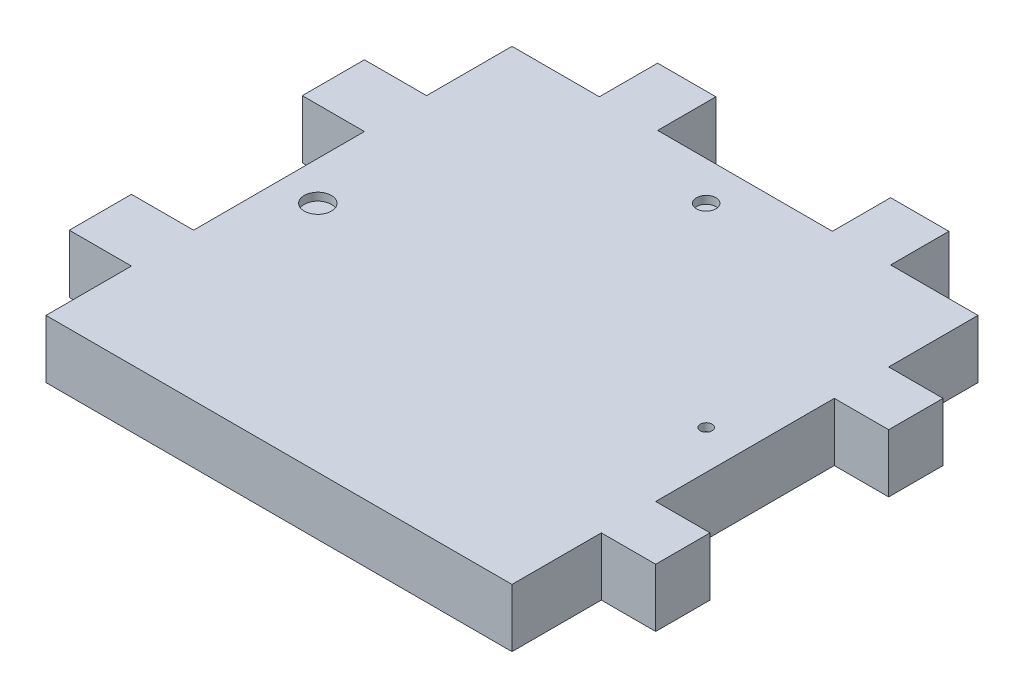
SolidWorks part; units mm, degrees
ref_plane "Front Plane" through (0, 0, 0) normal (0, 0, 1) x (1, 0, 0)
ref_plane "Top Plane" through (0, 0, 0) normal (0, 1, 0) x (1, 0, 0)
ref_plane "Right Plane" through (0, 0, 0) normal (1, 0, 0) x (0, 0, -1)
sketch "Sketch1" plane through (0, 0, 0) normal (0, 1, 0) x (1, 0, 0)
  line L0 (-28.575, 95.25) -> (28.575, 95.25) construction
  line L1 (76.2, 76.2) -> (-76.2, 76.2)
  line L2 (76.2, 76.2) -> (76.2, -76.2)
  line L3 (76.2, -76.2) -> (-76.2, -76.2)
  line L4 (-76.2, 76.2) -> (-76.2, -76.2)
  line L5 (76.2, 76.2) -> (-76.2, -76.2) construction
  line L6 (76.2, -76.2) -> (-76.2, 76.2) construction
  line L7 (-47.625, 76.2) -> (-28.575, 76.2)
  line L8 (-47.625, 76.2) -> (-47.625, 95.25)
  line L9 (-47.625, 95.25) -> (-28.575, 95.25)
  line L10 (-28.575, 76.2) -> (-28.575, 95.25)
  line L11 (28.575, 76.2) -> (47.625, 76.2)
  line L12 (28.575, 76.2) -> (28.575, 95.25)
  line L13 (28.575, 95.25) -> (47.625, 95.25)
  line L14 (47.625, 76.2) -> (47.625, 95.25)
  line L15 (-76.2, 48.26) -> (-96.52, 48.26)
  line L16 (-76.2, 48.26) -> (-76.2, 27.94)
  line L17 (-76.2, 27.94) -> (-96.52, 27.94)
  line L18 (-96.52, 48.26) -> (-96.52, 27.94)
  line L19 (-76.2, -27.94) -> (-96.52, -27.94)
  line L20 (-76.2, -27.94) -> (-76.2, -48.26)
  line L21 (-76.2, -48.26) -> (-96.52, -48.26)
  line L22 (-96.52, -27.94) -> (-96.52, -48.26)
  line L23 (76.2, 46.99) -> (93.98, 46.99)
  line L24 (76.2, 46.99) -> (76.2, 29.21)
  line L25 (76.2, 29.21) -> (93.98, 29.21)
  line L26 (93.98, 46.99) -> (93.98, 29.21)
  line L27 (76.2, -29.21) -> (93.98, -29.21)
  line L28 (76.2, -29.21) -> (76.2, -46.99)
  line L29 (76.2, -46.99) -> (93.98, -46.99)
  line L30 (93.98, -29.21) -> (93.98, -46.99)
  line L31 (-96.52, 48.26) -> (-96.52, -48.26) construction
  line L32 (93.98, -29.21) -> (93.98, 29.21) construction
  point P0 (0, 0)
  point P30 (93.98, 0)
  point P31 (-96.52, 0)
  point P32 (0, 95.25)
  dimension "D1" = 152.4
  dimension "D2" = 152.4
  dimension "D3" = 19.05
  dimension "D4" = 19.05
  dimension "D5" = 76.2
  dimension "D6" = 20.32
  dimension "D7" = 76.2
  dimension "D8" = 17.78
  dimension "D9" = 76.2
extrude "Boss-Extrude1" add sketch "Sketch1" along normal blind 19.05 contours L1 L4 L3 L2 | L19 L22 L21 L4 | L15 L18 L17 L4 | L1 L10 L9 L8 | L1 L14 L13 L12 | L26 L23 L2 L25 | L30 L27 L2 L29
sketch "Sketch2" plane through (0, 19.05, 0) normal (0, 1, 0) x (1, 0, 0)
  line L0 (28.575, 76.2) -> (-28.575, 76.2) construction
  line L1 (-76.2, 27.94) -> (-76.2, -27.94) construction
  line L2 (76.2, 29.21) -> (76.2, -29.21) construction
  circle A0 centre (63.5, 0) radius 1.905
  circle A1 centre (0, 63.5) radius 3.175
  circle A2 centre (-63.5, 0) radius 4.445
  point P12 (-63.5, 0)
  dimension "D1" = 3.81
  dimension "D2" = 6.35
  dimension "D3" = 8.89
  dimension "D4" = 12.7
  dimension "D5" = 12.7
  dimension "D6" = 12.7
extrude "Cut-Extrude1" cut sketch "Sketch2" against normal blind 2.54
